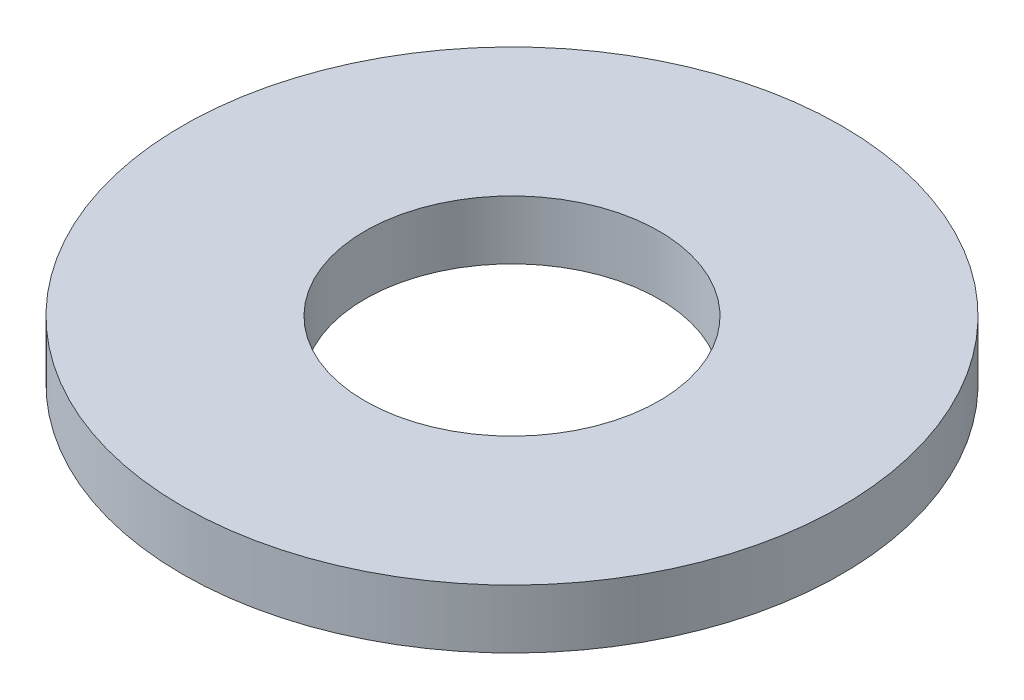
SolidWorks part; units mm, degrees
material "Plain Carbon Steel"
ref_plane "Front Plane" through (0, 0, 0) normal (0, 0, 1) x (1, 0, 0)
ref_plane "Top Plane" through (0, 0, 0) normal (0, 1, 0) x (1, 0, 0)
ref_plane "Right Plane" through (0, 0, 0) normal (1, 0, 0) x (0, 0, -1)
sketch "Sketch1" plane through (0, 0, 0) normal (0, 1, 0) x (1, 0, 0)
  circle A0 centre (0, 0) radius 7.9375
  circle A1 centre (0, 0) radius 17.78
  dimension "D1" = 15.875
  dimension "D2" = 35.56
extrude "Boss-Extrude1" add sketch "Sketch1" along normal blind 3.175
